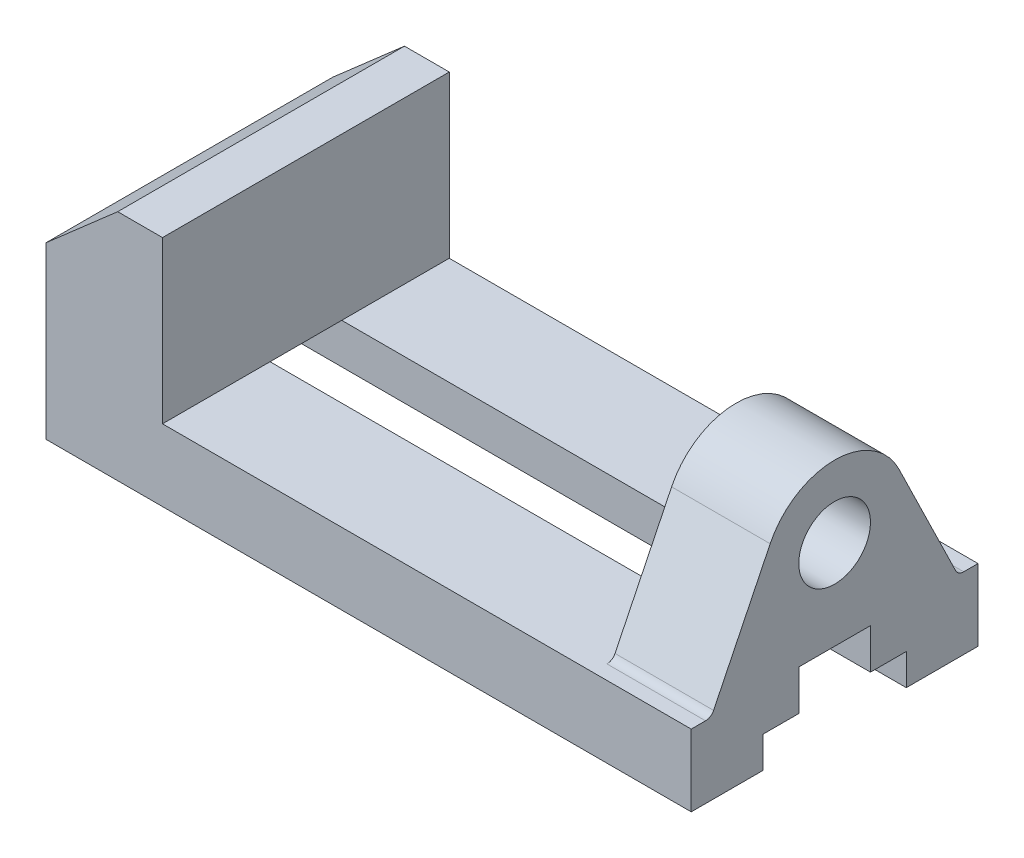
SolidWorks part; units mm, degrees
ref_plane "Front Plane" through (0, 0, 0) normal (0, 0, 1) x (1, 0, 0)
ref_plane "Top Plane" through (0, 0, 0) normal (0, 1, 0) x (1, 0, 0)
ref_plane "Right Plane" through (0, 0, 0) normal (1, 0, 0) x (0, 0, -1)
sketch "Sketch1" plane through (0, 0, 0) normal (0, 1, 0) x (1, 0, 0)
  line L1 (-72, 32) -> (72, 32)
  line L2 (-72, 32) -> (-72, -32)
  line L3 (-72, -32) -> (72, -32)
  line L4 (72, 32) -> (72, -32)
  line L5 (-72, 32) -> (72, -32) construction
  line L6 (-72, -32) -> (72, 32) construction
  point P0 (0, 0)
  dimension "D1" = 144
  dimension "D2" = 64
extrude "Boss-Extrude1" add sketch "Sketch1" along normal blind 16
sketch "Sketch2" plane through (0, 0, 32) normal (0, 0, 1) x (1, 0, 0)
  line L0 (-72, 16) -> (-72, 38)
  line L1 (-72, 38) -> (-56, 52)
  line L2 (-56, 52) -> (-46, 52)
  line L3 (-46, 52) -> (-46, 16)
  line L4 (-72, 16) -> (72, 16) construction
  line L5 (-46, 16) -> (-72, 16)
  line L6 (-72, 0) -> (72, 0) construction
  dimension "D1" = 14
  dimension "D2" = 10
  dimension "D3" = 16
  dimension "D4" = 52
extrude "Boss-Extrude2" add sketch "Sketch2" against normal blind 64
sketch "Sketch3" plane through (72, 0, 0) normal (1, 0, 0) x (0, 0, -1)
  line L0 (0, 0) -> (0, 36) construction
  line L1 (-27.5563, 16) -> (-14.3807, 43.0139)
  line L2 (32, 16) -> (-32, 16) construction
  line L3 (14.3807, 43.0139) -> (27.5563, 16)
  line L4 (27.5563, 16) -> (-27.5563, 16)
  circle A0 centre (0, 36) radius 8
  arc A1 (-14.3807, 43.0139) -> (14.3807, 43.0139) centre (0, 36) cw
  point P1 (0, 0)
  point P10 (0, 0)
  dimension "D2" = 16
  dimension "D3" = 16
  dimension "D1" = 36
  dimension "D4" = 52
extrude "Boss-Extrude3" add sketch "Sketch3" against normal blind 22
fillet "Fillet1" radius 2 2 edges at (61, 16, -27.5563) (61, 16, 27.5563)
sketch "Sketch4" plane through (72, 0, 0) normal (1, 0, 0) x (0, 0, -1)
  line L0 (0, 0) -> (0, 16.694) construction
  line L1 (-16, 0) -> (-16, 7)
  line L2 (-32, 0) -> (32, 0) construction
  line L3 (-16, 7) -> (-8, 7)
  line L4 (-8, 7) -> (-8, 16)
  line L5 (-8, 16) -> (8, 16)
  line L6 (-16, 0) -> (16, 0)
  line L7 (16, 0) -> (16, 7)
  line L8 (16, 7) -> (8, 7)
  line L9 (8, 7) -> (8, 16)
  point P14 (0, 16)
  dimension "D1" = 16
  dimension "D2" = 8
  dimension "D3" = 7
  dimension "D4" = 9
extrude "Cut-Extrude1" cut sketch "Sketch4" against normal through all
sketch "Sketch5" plane through (0, 0, 0) normal (0, -1, 0) x (1, 0, 0)
  line L0 (-72, 32) -> (72, 32) construction
  line L1 (72, -32) -> (-72, -32) construction
  line L2 (72, -16) -> (72, -32) construction
  point P0 (-36, 22)
  point P1 (36, 22)
  point P2 (36, -22)
  point P3 (-36, -22)
  point P11 (0, 0)
  point P12 (0, 0)
  point P13 (0, 0)
  dimension "D1" = 10
  dimension "D2" = 44
  dimension "D3" = 10
  dimension "D4" = 36
  dimension "D5" = 72
